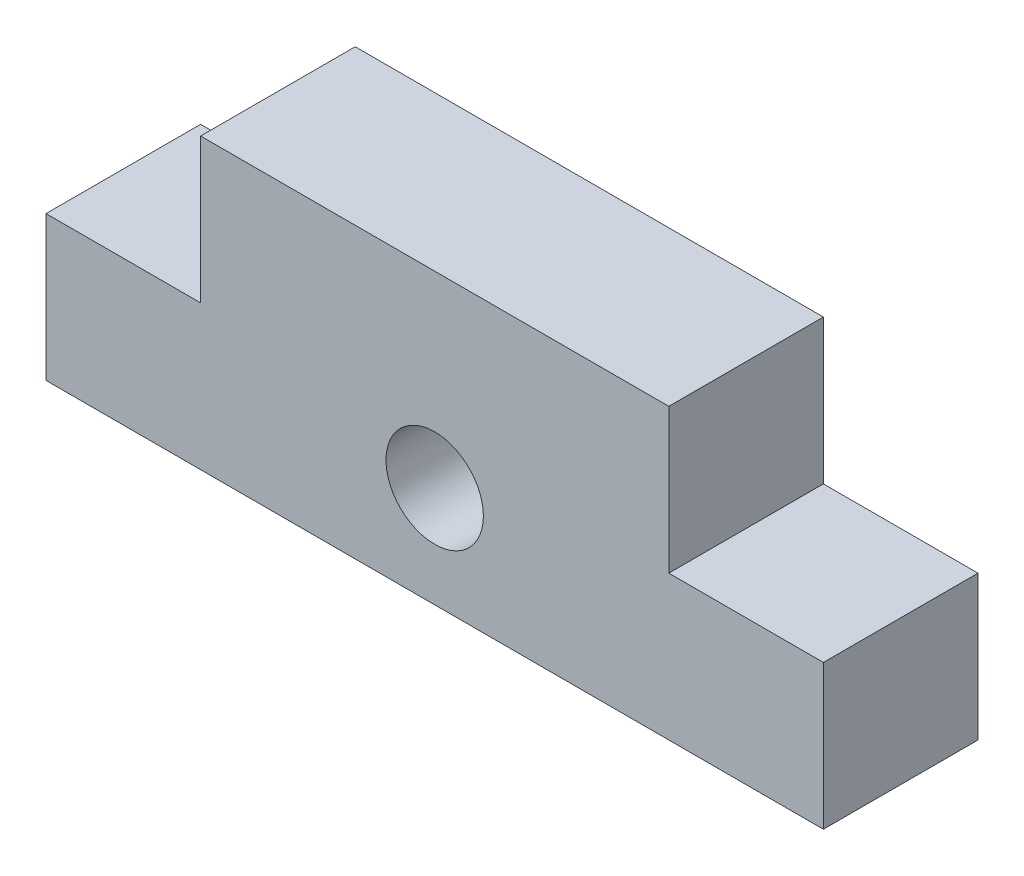
SolidWorks part; units mm, degrees
ref_plane "Front Plane" through (0, 0, 0) normal (0, 0, 1) x (1, 0, 0)
ref_plane "Top Plane" through (0, 0, 0) normal (0, 1, 0) x (1, 0, 0)
ref_plane "Right Plane" through (0, 0, 0) normal (1, 0, 0) x (0, 0, -1)
sketch "Model" plane through (0, 0, 0) normal (0, 0, 1) x (1, 0, 0)
  line L0 (13.45, 0) -> (13.45, 14.6144) construction
  line L1 (0, 0) -> (26.9, 0)
  line L2 (0, 0) -> (0, 5)
  line L3 (0, 5) -> (5.35, 5)
  line L4 (26.9, 0) -> (26.9, 5)
  line L5 (21.55, 5) -> (26.9, 5)
  line L6 (5.35, 10) -> (21.55, 10)
  line L7 (5.35, 10) -> (5.35, 5)
  line L9 (21.55, 10) -> (21.55, 5)
  line L10 (5.35, 10) -> (21.55, 5) construction
  line L11 (5.35, 5) -> (21.55, 10) construction
  circle A0 centre (13.45, 3.5) radius 1.685
  point P6 (13.45, 7.5)
  dimension "D9" = 3.37
  dimension "D2" = 26.9
  dimension "D4" = 5
  dimension "D6" = 5
  dimension "D12" = 3.5
  dimension "D3" = 5.35
extrude "Boss-Extrude1" add sketch "Model" along normal blind 5.35
equation "\"mdfthick\"=5.35"
equation "\"D3@Model\"=\"mdfthick\""
equation "\"D1@Boss-Extrude1\"=\"mdfthick\""
